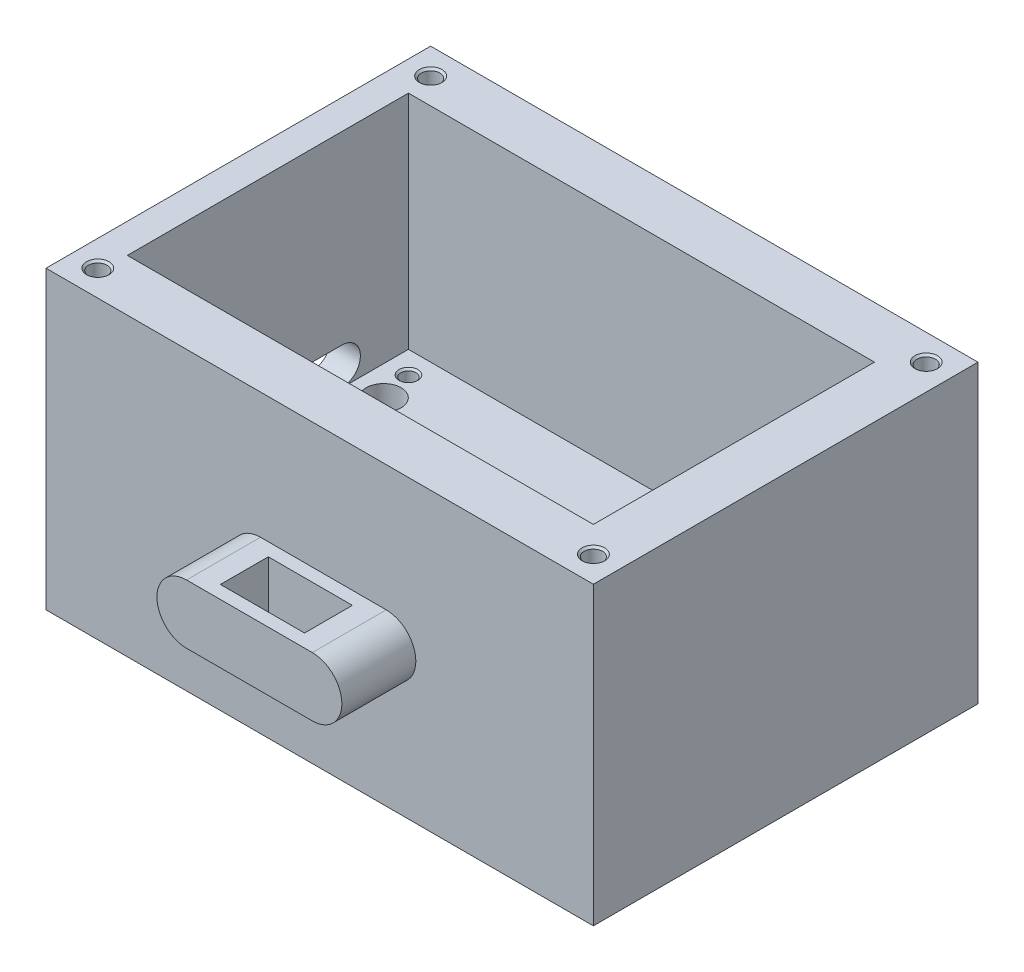
SolidWorks part; units mm, degrees
ref_plane "Front Plane" through (0, 0, 0) normal (0, 0, 1) x (1, 0, 0)
ref_plane "Top Plane" through (0, 0, 0) normal (0, 1, 0) x (1, 0, 0)
ref_plane "Right Plane" through (0, 0, 0) normal (1, 0, 0) x (0, 0, -1)
sketch "Sketch1" plane through (0, 0, 0) normal (0, 1, 0) x (1, 0, 0)
  line L1 (-37, -26) -> (37, -26)
  line L2 (-37, -26) -> (-37, 26)
  line L3 (-37, 26) -> (37, 26)
  line L4 (37, -26) -> (37, 26)
  line L5 (-37, -26) -> (37, 26) construction
  line L6 (-37, 26) -> (37, -26) construction
  point P0 (0, 0)
  dimension "D1" = 74
  dimension "D2" = 52
extrude "Boss-Extrude2" add sketch "Sketch1" along normal blind 40
shell "Shell3" thickness 7
sketch "Sketch4" plane through (0, 40, 0) normal (0, 1, 0) x (1, 0, 0)
  line L0 (-37, 26) -> (-37, -26) construction
  line L1 (37, 26) -> (-37, 26) construction
  line L2 (37, -26) -> (37, 26) construction
  line L3 (-37, -26) -> (37, -26) construction
  point P0 (-33.5, 22.5)
  point P1 (33.5, 22.5)
  point P2 (33.5, -22.5)
  point P3 (-33.5, -22.5)
  dimension "D1" = 3.5
  dimension "D2" = 3.5
  dimension "D3" = 3.5
  dimension "D4" = 3.5
hole_wizard "M3 Tapped Hole1" positions "Sketch5" profile "Sketch7" tap size "M3" standard "ISO"
sketch "Sketch5" plane through (0, 40, 0) normal (0, 1, 0) x (1, 0, 0)
  point P0 (-33.5, 22.5)
  point P3 (-33.5, -22.5)
  point P6 (33.5, -22.5)
  point P9 (33.5, 22.5)
sketch "Sketch7" plane through (-33.5, 40, -22.5) normal (1, 0, 0) x (0, 0, 1)
  line L0 (0, 0) -> (0, 4.7511)
  line L1 (0, 4.7511) -> (1.25, 4)
  line L2 (1.25, 4) -> (1.25, 0.275)
  line L3 (1.25, 0.275) -> (1.525, 0)
  line L5 (1.525, 0) -> (0, 0)
  line L6 (-1.25, 0.275) -> (-1.525, 0) construction
  line L10 (0, 4.7511) -> (-1.25, 4) construction
  line L11 (0, -6.35) -> (0, 107.95) construction
  dimension "Tap Drill Dia." = 2.5
  dimension "Tap Drill Depth" = 4
  dimension "Near C'Sink Dia." = 3.05
  dimension "Near C'Sink Angle" = 90
  dimension "Drill Angle" = 118
cosmetic thread "Hole Thread1" parameters "D1"=5, "D2"=3
cosmetic thread "Hole Thread2" parameters "D1"=5, "D2"=3
cosmetic thread "Hole Thread3" parameters "D1"=5, "D2"=3
cosmetic thread "Hole Thread4" parameters "D1"=5, "D2"=3
sketch "Sketch8" plane through (0, 10, 0) normal (0, 1, 0) x (1, 0, 0)
  line L0 (-33, 19) -> (-33, -19) construction
  line L1 (30, 19) -> (-33, 19) construction
  line L2 (30, 19) -> (-33, 19) construction
  point P0 (-30, 16)
  point P1 (-30, -7)
  point P2 (17, -7)
  point P3 (17, 16)
  point P4 (-30, -7)
  point P5 (17, -7)
  point P14 (-30, -7)
  dimension "D1" = 3
  dimension "D2" = 3
  dimension "D3" = 3
  dimension "D4" = 3
  dimension "D5" = 23
  dimension "D6" = 47
hole_wizard "M2.5 Tapped Hole1" positions "Sketch10" profile "Sketch11" tap size "M2.5" standard "ISO"
sketch "Sketch10" plane through (0, 10, 0) normal (0, 1, 0) x (1, 0, 0)
  point P0 (-30, 16)
  point P3 (-30, -7)
  point P6 (17, -7)
  point P9 (17, 16)
sketch "Sketch11" plane through (-30, 10, -16) normal (1, 0, 0) x (0, 0, 1)
  line L0 (0, 0) -> (0, 5.1159)
  line L1 (0, 5.1159) -> (1.025, 4.5)
  line L2 (1.025, 4.5) -> (1.025, 0.25)
  line L3 (1.025, 0.25) -> (1.275, 0)
  line L5 (1.275, 0) -> (0, 0)
  line L6 (-1.025, 0.25) -> (-1.275, 0) construction
  line L10 (0, 5.1159) -> (-1.025, 4.5) construction
  line L11 (0, -6.35) -> (0, 107.95) construction
  dimension "Tap Drill Dia." = 2.05
  dimension "Tap Drill Depth" = 4.5
  dimension "Near C'Sink Dia." = 2.55
  dimension "Near C'Sink Angle" = 90
  dimension "Drill Angle" = 118
cosmetic thread "Hole Thread5" parameters "D1"=5, "D2"=2.5
cosmetic thread "Hole Thread6" parameters "D1"=5, "D2"=2.5
cosmetic thread "Hole Thread7" parameters "D1"=5, "D2"=2.5
cosmetic thread "Hole Thread8" parameters "D1"=5, "D2"=2.5
sketch "Sketch12" plane through (-33, 0, 0) normal (1, 0, 0) x (0, 0, -1)
  point P7 (-7, 12.6)
  point P8 (16, 12.6)
  dimension "D1" = 2.6
sketch "Sketch15" plane through (-33, 0, 0) normal (1, 0, 0) x (0, 0, -1)
  line L1 (-1, 12.5) -> (10, 12.5) construction
  line L2 (-1, 15) -> (10, 15)
  line L3 (-1, 10) -> (10, 10)
  arc A0 (-1, 15) -> (-1, 10) centre (-1, 12.5) ccw
  arc A1 (10, 10) -> (10, 15) centre (10, 12.5) ccw
  point P4 (4.5, 12.5)
  dimension "D1" = 11
  dimension "D2" = 0
  dimension "D3" = 5
extrude "Cut-Extrude2" cut sketch "Sketch15" against normal blind 40 contours L2 A1 L3 A0
sketch "Sketch24" plane through (0, 10, 0) normal (0, 1, 0) x (1, 0, 0)
  circle A0 centre (-29.0045, 11.6545) radius 2.3585
  circle A3 centre (-29.0045, -2.6545) radius 2.3585
extrude "Cut-Extrude3" cut sketch "Sketch24" against normal blind 40
sketch "Sketch26" plane through (0, 0, 0) normal (0, -1, 0) x (1, 0, 0)
sketch "Sketch28" plane through (0, 0, 0) normal (0, -1, 0) x (1, 0, 0)
  text T0 "<b><i>Boot</i></b>"
  text T1 "<b><i>En</i></b>"
extrude "Cut-Extrude4" cut sketch "Sketch28" against normal blind 1
sketch "Sketch45" plane through (0, 0, 26) normal (0, 0, 1) x (1, 0, 0)
  line L0 (-8, 19) -> (9, 19) construction
  line L1 (-8, 23) -> (9, 23)
  line L2 (-8, 15) -> (9, 15)
  line L3 (-37, 40) -> (37, 40) construction
  line L4 (-37, 40) -> (-37, 0) construction
  arc A0 (-8, 23) -> (-8, 15) centre (-8, 19) ccw
  arc A1 (9, 15) -> (9, 23) centre (9, 19) ccw
  point P2 (0.5, 19)
  point P7 (0, 0)
  point P10 (-12, 19)
  dimension "D1" = 8
  dimension "D2" = 17
  dimension "D3" = 17
  dimension "D4" = 25
sketch "Sketch48" plane through (0, 0, -26) normal (0, 0, -1) x (-1, 0, 0)
  line L0 (-9, 19) -> (8, 19) construction
  line L1 (-9, 23) -> (8, 23)
  line L2 (-9, 15) -> (8, 15)
  line L3 (-37, 40) -> (-37, 0) construction
  arc A0 (-9, 23) -> (-9, 15) centre (-9, 19) ccw
  arc A1 (8, 15) -> (8, 23) centre (8, 19) ccw
  point P2 (-0.5, 19)
  point P9 (-13, 19)
  dimension "D1" = 8
  dimension "D2" = 24
extrude "Boss-Extrude4" add sketch "Sketch48" along normal blind 10
extrude "Boss-Extrude5" add sketch "Sketch45" along normal blind 10
sketch "Sketch50" plane through (0, 23, 0) normal (0, 1, 0) x (1, 0, 0)
  line L0 (-8, 31) -> (9, 31) construction
  line L1 (-8, 36) -> (-8, 26) construction
  line L2 (9, 36) -> (9, 26) construction
  line L3 (-8, -31) -> (9, -31) construction
  line L4 (-8, -36) -> (-8, -26) construction
  line L5 (9, -36) -> (9, -26) construction
  line L6 (-37, 0) -> (37.5717, 0) construction
  line L7 (-5.1865, 34.2362) -> (6.1865, 34.2362)
  line L8 (-5.1865, 34.2362) -> (-5.1865, 27.7638)
  line L9 (-5.1865, 27.7638) -> (6.1865, 27.7638)
  line L10 (6.1865, 34.2362) -> (6.1865, 27.7638)
  line L11 (-5.1865, 34.2362) -> (6.1865, 27.7638) construction
  line L12 (-5.1865, 27.7638) -> (6.1865, 34.2362) construction
  line L13 (-37, 26) -> (-37, -26) construction
  line L14 (6.1865, -34.2362) -> (6.1865, -27.7638)
  line L15 (-5.1865, -34.2362) -> (6.1865, -27.7638) construction
  line L16 (-5.1865, -27.7638) -> (6.1865, -27.7638)
  line L17 (-5.1865, -34.2362) -> (-5.1865, -27.7638)
  line L18 (-5.1865, -34.2362) -> (6.1865, -34.2362)
  line L19 (-8, -31) -> (9, -31) construction
  line L20 (-5.1865, -27.7638) -> (6.1865, -34.2362) construction
  point P12 (0.5, 31)
extrude "Cut-Extrude6" cut sketch "Sketch50" against normal blind 10
equation "\"D2@Sketch4\"=\"D1@Sketch4\""
equation "\"D3@Sketch4\"=\"D1@Sketch4\""
equation "\"D4@Sketch4\"=\"D1@Sketch4\""
equation "\"D2@Sketch8\"=\"D1@Sketch8\""
